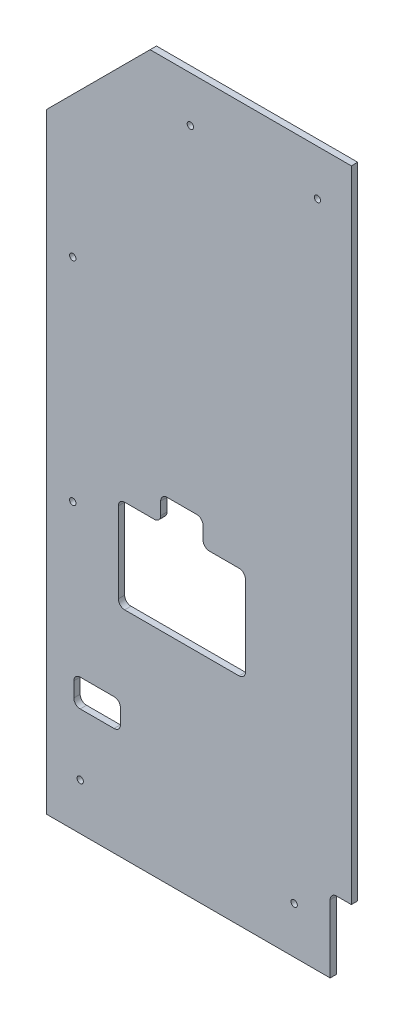
SolidWorks part; units mm, degrees
ref_plane "Front" through (0, 0, 0) normal (0, 0, 1) x (1, 0, 0)
ref_plane "Top" through (0, 0, 0) normal (0, 1, 0) x (1, 0, 0)
ref_plane "Right" through (0, 0, 0) normal (1, 0, 0) x (0, 0, -1)
sketch "Esquisse1" plane through (0, 0, 0) normal (0, 0, 1) x (1, 0, 0)
  line L1 (0, 0) -> (144, 0)
  line L2 (0, 0) -> (0, 337)
  line L3 (0, 337) -> (144, 337)
  line L4 (144, 0) -> (144, 337)
  dimension "D1" = 144
  dimension "D2" = 337
extrude "Boss.-Extru.1" add sketch "Esquisse1" along normal blind 3
sketch "Esquisse2" plane through (0, 0, 3) normal (0, 0, 1) x (1, 0, 0)
  line L0 (0, 22) -> (16, 22) construction
  line L1 (0, 337) -> (0, 0) construction
  line L2 (0, 0) -> (144, 0) construction
  line L3 (12.5, 134) -> (12.5, 234) construction
  line L4 (68, 315.5) -> (128, 315.5) construction
  line L5 (72, 0) -> (72, 12.3457) construction
  line L6 (16, 22) -> (117, 22) construction
  circle A0 centre (16, 22) radius 1.5
  circle A1 centre (12.5, 234) radius 1.5
  circle A2 centre (12.5, 134) radius 1.5
  circle A3 centre (68, 315.5) radius 1.5
  circle A4 centre (128, 315.5) radius 1.5
  circle A5 centre (117, 22) radius 1.5
  dimension "D1" = 3
  dimension "D7" = 55.5
  dimension "D10" = 45
  dimension "D2" = 16
  dimension "D3" = 22
  dimension "D4" = 112
  dimension "D5" = 3.5
  dimension "D6" = 100
  dimension "D8" = 81.5
  dimension "D9" = 60
extrude "Enlèv. mat.-Extru.1" cut sketch "Esquisse2" against normal through all
chamfer "Chanfrein1" distance 49 angle 45 1 edges at (0, 337, 1.5)
sketch "Esquisse3" plane through (0, 0, 3) normal (0, 0, 1) x (1, 0, 0)
  line L0 (144, 0) -> (144, 337) construction
  line L1 (0, 0) -> (144, 0) construction
  line L2 (134, 0) -> (144, 0)
  line L3 (134, 0) -> (134, 35)
  line L4 (134, 35) -> (144, 35)
  line L5 (144, 0) -> (144, 35)
  dimension "D1" = 10
  dimension "D2" = 35
extrude "Enlèv. mat.-Extru.2" cut sketch "Esquisse3" against normal through all and the other way through all
sketch "Esquisse4" plane through (0, 0, 3) normal (0, 0, 1) x (1, 0, 0)
  line L0 (0, 288) -> (0, 0) construction
  line L1 (13, 64) -> (35, 64)
  line L2 (13, 64) -> (13, 51)
  line L3 (13, 51) -> (35, 51)
  line L4 (35, 64) -> (35, 51)
  line L5 (0, 0) -> (134, 0) construction
  dimension "D1" = 13
  dimension "D2" = 22
  dimension "D3" = 13
  dimension "D4" = 51
extrude "Enlèv. mat.-Extru.3" cut sketch "Esquisse4" against normal through all
sketch "Esquisse5" plane through (0, 0, 3) normal (0, 0, 1) x (1, 0, 0)
  line L0 (144, 60) -> (90, 60)
  line L1 (144, 35) -> (144, 337) construction
  line L2 (90, 60) -> (90, 190)
  line L3 (144, 60) -> (144, 296.5764)
  line L4 (0, 0) -> (134, 0) construction
  arc A0 (90, 190) -> (144, 296.5764) centre (121.9959, 240.7569) cw
  dimension "D4" = 60
  dimension "D1" = 54
  dimension "D2" = 60
  dimension "D3" = 130
extrude "Enlèv. mat.-Extru.4" cut sketch "Esquisse5" against normal through all
sketch "Esquisse6" [suppressed] plane through (0, 0, 3) normal (0, 0, 1) x (1, 0, 0)
  line L0 (144, 35) -> (144, 337) construction
  line L1 (74, 102) -> (134, 102)
  line L2 (74, 102) -> (74, 158)
  line L3 (74, 158) -> (134, 158)
  line L4 (134, 102) -> (134, 158)
  line L5 (0, 0) -> (134, 0) construction
  dimension "D1" = 60
  dimension "D2" = 10
  dimension "D3" = 102
  dimension "D4" = 56
extrude "Enlèv. mat.-Extru.5" [suppressed] cut sketch "Esquisse6" against normal through all
sketch "Esquisse7" [suppressed] plane through (0, 0, 3) normal (0, 0, 1) x (1, 0, 0)
  line L0 (74, 158) -> (74, 102) construction
  line L1 (74, 146) -> (94, 146)
  line L2 (74, 146) -> (74, 158)
  line L3 (74, 158) -> (94, 158)
  line L4 (94, 146) -> (94, 158)
  line L5 (134, 158) -> (74, 158) construction
  line L6 (104, 158) -> (104, 134.3616) construction
  line L7 (114, 146) -> (114, 158)
  line L8 (134, 158) -> (114, 158)
  line L9 (134, 146) -> (134, 158)
  line L10 (134, 146) -> (114, 146)
  dimension "D1" = 20
  dimension "D2" = 12
extrude "Boss.-Extru.2" [suppressed] add sketch "Esquisse7" against normal up to vertex
sketch "Esquisse8" [suppressed] plane through (0, 0, 3) normal (0, 0, 1) x (1, 0, 0)
  line L0 (0, 0) -> (134, 0) construction
  line L1 (64, 86) -> (84, 86)
  line L2 (64, 86) -> (64, 70)
  line L3 (64, 70) -> (84, 70)
  line L4 (84, 86) -> (84, 70)
  line L5 (0, 288) -> (0, 0) construction
  dimension "D1" = 20
  dimension "D2" = 16
  dimension "D3" = 70
  dimension "D4" = 64
extrude "Enlèv. mat.-Extru.6" [suppressed] cut sketch "Esquisse8" against normal through all
fillet "Congé1" [suppressed] radius 3
sketch "Esquisse9" plane through (0, 0, 3) normal (0, 0, 1) x (1, 0, 0)
  line L0 (94, 102) -> (34, 102)
  line L1 (94, 102) -> (94, 146)
  line L2 (94, 146) -> (74, 146)
  line L3 (74, 146) -> (74, 158)
  line L4 (74, 158) -> (54, 158)
  line L5 (64, 158) -> (64, 102) construction
  line L6 (54, 146) -> (54, 158)
  line L7 (34, 146) -> (54, 146)
  line L8 (34, 102) -> (34, 146)
  line L9 (0, 288) -> (0, 0) construction
  dimension "D1" = 20
  dimension "D2" = 56
  dimension "D3" = 12
  dimension "D4" = 60
  dimension "D5" = 34
  dimension "D6" = 102
extrude "Enlèv. mat.-Extru.7" cut sketch "Esquisse9" against normal through all
fillet "Congé2" [suppressed] radius 3
fillet "Congé3" [suppressed] radius 10
sketch "Esquisse10" plane through (0, 0, 3) normal (0, 0, 1) x (1, 0, 0)
  line L0 (144, 60) -> (90, 60)
  line L1 (90, 60) -> (90, 102)
  line L2 (90, 190) -> (55, 190)
  line L3 (55, 190) -> (55, 302)
  line L4 (55, 302) -> (144, 302)
  line L5 (144, 296.5764) -> (144, 337) construction
  line L6 (144, 302) -> (144, 60)
  line L7 (90, 102) -> (94, 102)
  line L8 (94, 102) -> (94, 146)
  line L9 (94, 146) -> (90, 146)
  line L10 (90, 146) -> (90, 190)
  line L11 (34, 146) -> (34, 102) construction
  dimension "D1" = 112
  dimension "D2" = 35
  dimension "D3" = 60
extrude "Boss.-Extru.3" add sketch "Esquisse10" against normal up to vertex (3 mm away)
fillet "Congé4" radius 3 13 edges at (134, 35, 1.5) (13, 64, 1.5) (13, 51, 1.5) (35, 51, 1.5) (35, 64, 1.5) (94, 102, 1.5) (94, 146, 1.5) (74, 146, 1.5) (74, 158, 1.5) (54, 158, 1.5) (54, 146, 1.5) (34, 146, 1.5) (34, 102, 1.5)
